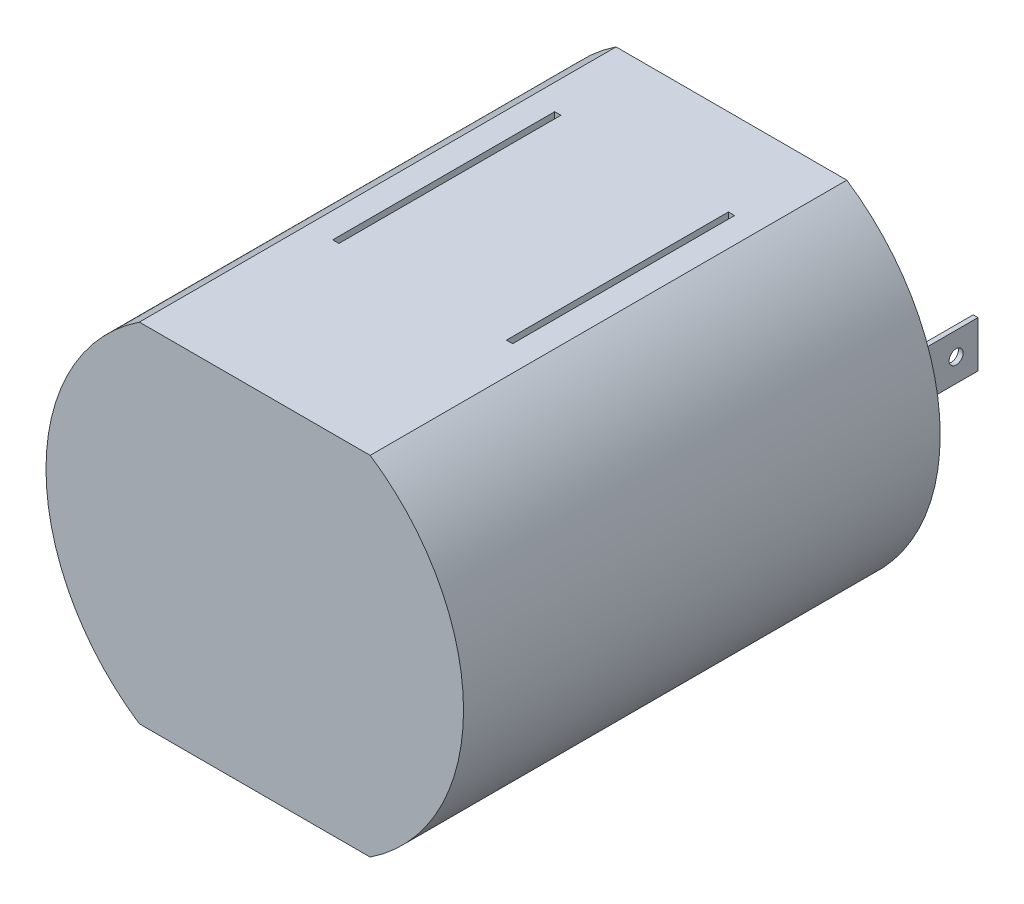
SolidWorks part; units mm, degrees
ref_plane "Front Plane" through (0, 0, 0) normal (0, 0, 1) x (1, 0, 0)
ref_plane "Top Plane" through (0, 0, 0) normal (0, 1, 0) x (1, 0, 0)
ref_plane "Right Plane" through (0, 0, 0) normal (1, 0, 0) x (0, 0, -1)
sketch "Sketch1" plane through (0, 0, 0) normal (0, 0, 1) x (1, 0, 0)
  line L1 (-3.3166, -5) -> (3.3166, -5)
  line L3 (-3.3166, 5) -> (3.3166, 5)
  arc A0 (-3.3166, 5) -> (-3.3166, -5) centre (0, 0) ccw
  arc A1 (3.3166, -5) -> (3.3166, 5) centre (0, 0) ccw
  dimension "D1" = 12
extrude "Boss-Extrude1" add sketch "Sketch1" along normal blind 13.7
sketch "Sketch3" plane through (0, 5, 0) normal (0, 1, 0) x (1, 0, 0)
  line L0 (-2.4067, -8.8749) -> (-2.5852, -8.8749)
  line L2 (-2.4067, -2.494) -> (-2.5852, -2.494)
  line L3 (2.5852, -8.8749) -> (2.4067, -8.8749)
  line L7 (-2.5852, -2.494) -> (-2.5852, -8.8749)
  line L10 (-2.4067, -2.494) -> (-2.4067, -8.8749)
  line L16 (2.5852, -2.494) -> (2.4067, -2.494)
  line L26 (2.4067, -2.494) -> (2.4067, -8.8749)
  line L27 (2.5852, -2.494) -> (2.5852, -8.8749)
  point P0 (0, 0)
  point P9 (0, 0)
extrude "Cut-Extrude1" cut sketch "Sketch3" against normal blind 0.2
sketch "Sketch4" plane through (0, 0, 0) normal (0, 0, -1) x (-1, 0, 0)
  circle A0 centre (0, 0) radius 0.85 construction
  circle A1 centre (0, 0) radius 0.85
extrude "Boss-Extrude3" add sketch "Sketch4" along normal blind 1.8
sketch "Sketch5" plane through (0, 0, 0) normal (0, 0, -1) x (-1, 0, 0)
  line L0 (4.2866, 0.6646) -> (4.1485, -0.6646) construction
  line L2 (4.2866, -0.6646) -> (4.1485, 0.6646) construction
  line L3 (-4.2866, -0.6646) -> (-4.1485, -0.6646)
  line L4 (-4.2866, -0.6646) -> (-4.2866, 0.6646)
  line L5 (-4.2866, 0.6646) -> (-4.1485, 0.6646)
  line L6 (-4.1485, -0.6646) -> (-4.1485, 0.6646)
  line L7 (-4.2866, -0.6646) -> (-4.1485, 0.6646) construction
  line L8 (-4.2866, 0.6646) -> (-4.1485, -0.6646) construction
  line L9 (4.1485, -0.6646) -> (4.1485, 0.6646)
  line L10 (4.2866, 0.6646) -> (4.1485, 0.6646)
  line L11 (4.2866, -0.6646) -> (4.2866, 0.6646)
  line L12 (4.2866, -0.6646) -> (4.1485, -0.6646)
extrude "Boss-Extrude4" add sketch "Sketch5" along normal blind 2.8
sketch "Sketch6" plane through (-4.2866, 0, 0) normal (-1, 0, 0) x (0, 0, 1)
  circle A0 centre (-2.1717, 0) radius 0.202
extrude "Cut-Extrude2" cut sketch "Sketch6" against normal blind 9.6
